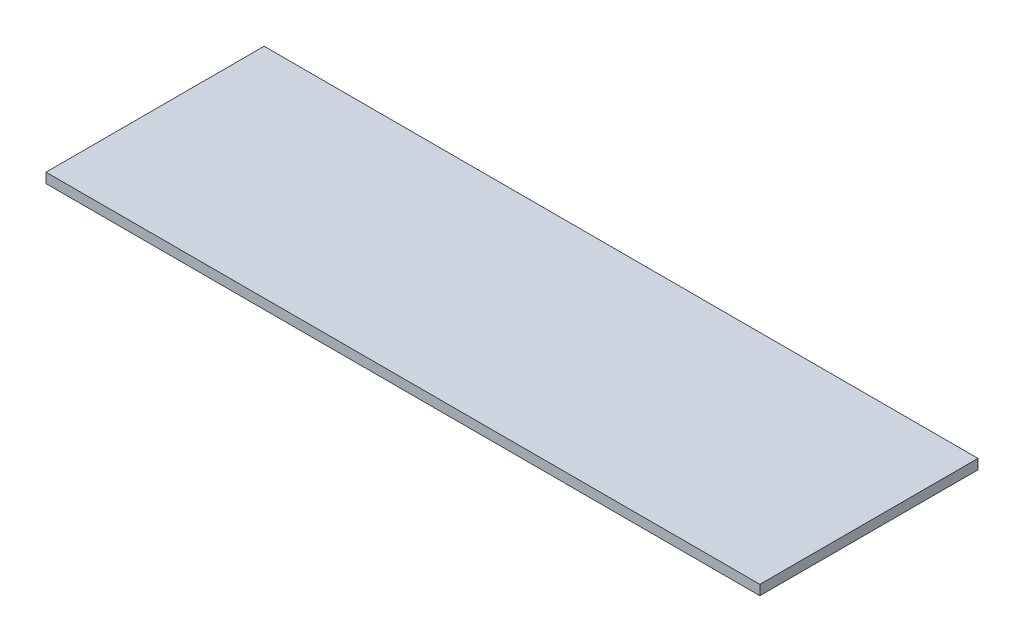
SolidWorks part; units mm, degrees
material "ASTM A36 Steel"
ref_plane "Front Plane" through (0, 0, 0) normal (0, 0, 1) x (1, 0, 0)
ref_plane "Top Plane" through (0, 0, 0) normal (0, 1, 0) x (1, 0, 0)
ref_plane "Right Plane" through (0, 0, 0) normal (1, 0, 0) x (0, 0, -1)
sketch "Sketch1" plane through (0, 0, 0) normal (0, 1, 0) x (1, 0, 0)
  line L1 (-114.3, -34.925) -> (114.3, -34.925)
  line L2 (-114.3, -34.925) -> (-114.3, 34.925)
  line L3 (-114.3, 34.925) -> (114.3, 34.925)
  line L4 (114.3, -34.925) -> (114.3, 34.925)
  line L5 (-114.3, -34.925) -> (114.3, 34.925) construction
  line L6 (-114.3, 34.925) -> (114.3, -34.925) construction
  line L7 (-114.3, 0) -> (114.3, 0) construction
  point P0 (0, 0)
  dimension "D1" = 228.6
  dimension "D2" = 69.85
extrude "Boss-Extrude1" add sketch "Sketch1" along normal blind 3.175
